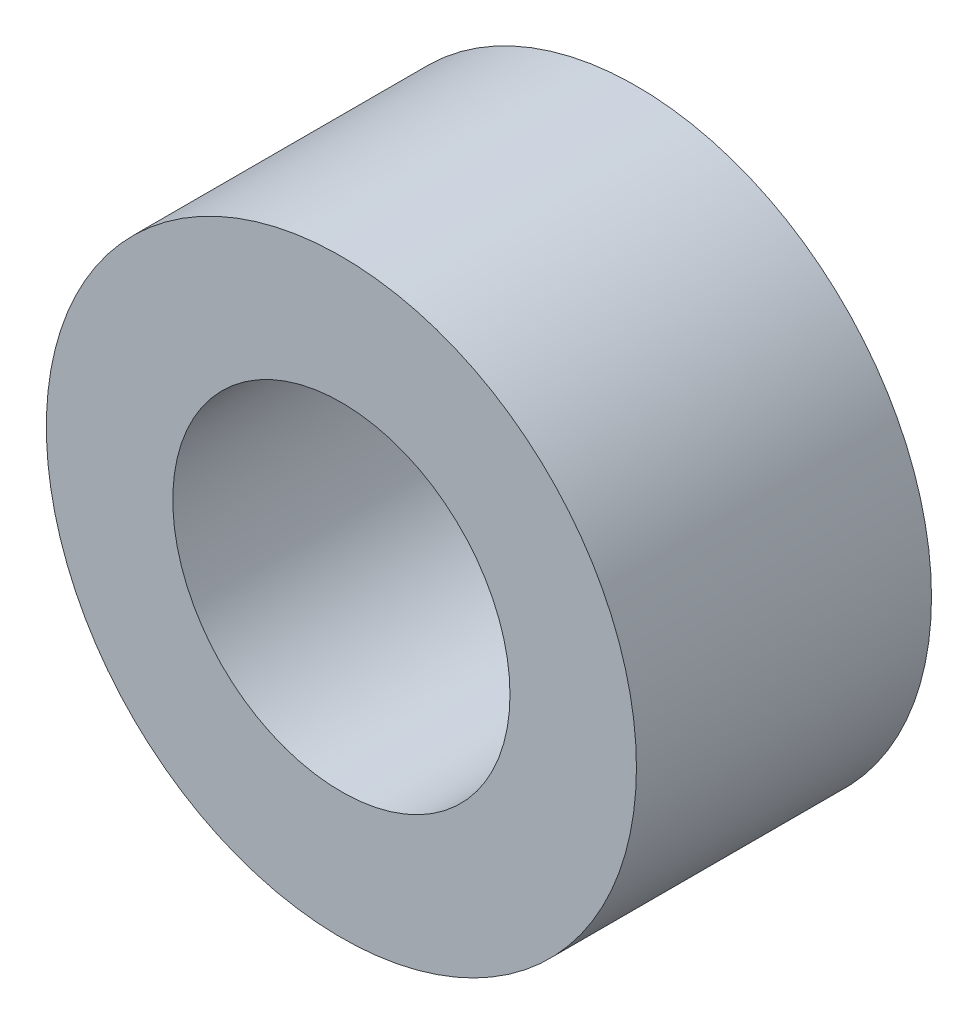
SolidWorks part; units mm, degrees
ref_plane "Front Plane" through (0, 0, 0) normal (0, 0, 1) x (1, 0, 0)
ref_plane "Top Plane" through (0, 0, 0) normal (0, 1, 0) x (1, 0, 0)
ref_plane "Right Plane" through (0, 0, 0) normal (1, 0, 0) x (0, 0, -1)
sketch "Sketch1" plane through (0, 0, 0) normal (0, 0, 1) x (1, 0, 0)
  circle A0 centre (0, 0) radius 7
  circle A1 centre (0, 0) radius 4
  dimension "D1" = 14
  dimension "D2" = 8
extrude "Boss-Extrude1" add sketch "Sketch1" along normal blind 7
